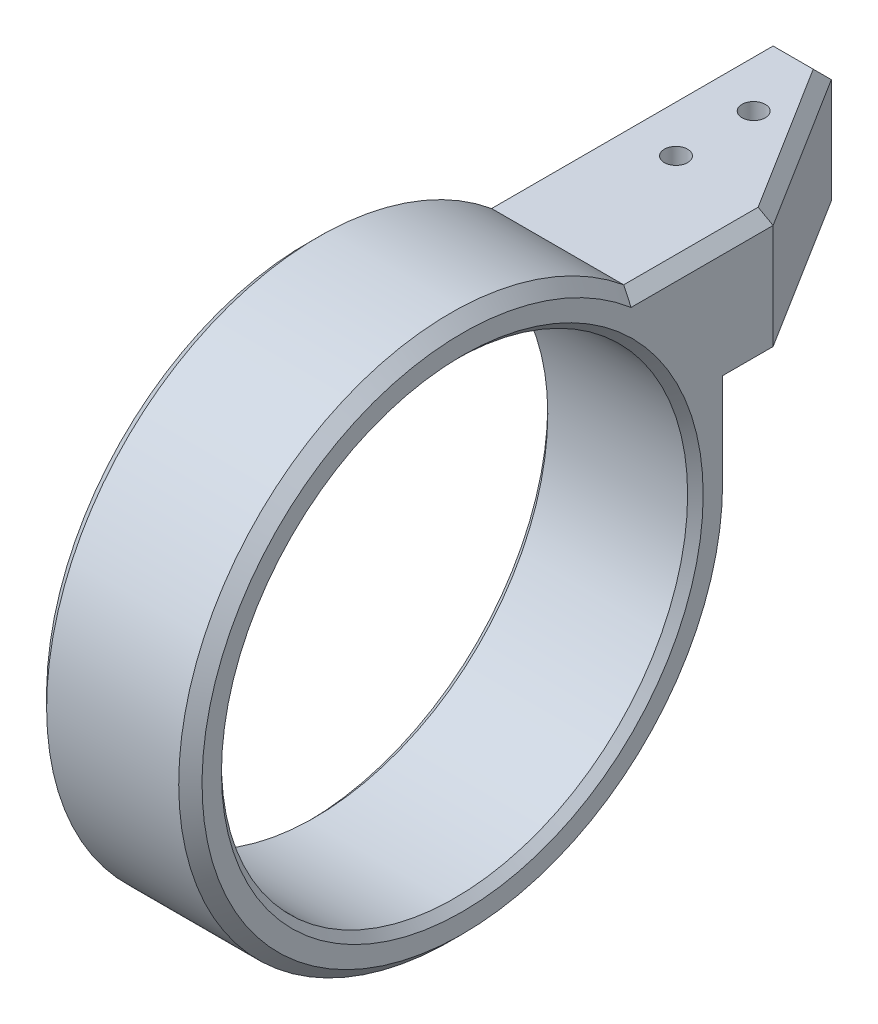
SolidWorks part; units mm, degrees
ref_plane "Front" through (0, 0, 0) normal (0, 0, 1) x (1, 0, 0)
ref_plane "Top" through (0, 0, 0) normal (0, 1, 0) x (1, 0, 0)
ref_plane "Right" through (0, 0, 0) normal (1, 0, 0) x (0, 0, -1)
sketch "草图1" plane through (0, 0, 0) normal (1, 0, 0) x (0, 0, -1)
  circle A0 centre (0, 0) radius 35
  dimension "D1" = 70
extrude "凸台-拉伸1" add sketch "草图1" along normal blind 20
sketch "草图2" plane through (20, 0, 0) normal (1, 0, 0) x (0, 0, -1)
  circle A0 centre (0, 0) radius 30
  circle A1 centre (0, 0) radius 35 construction
  dimension "D1" = 60
extrude "切除-拉伸1" cut sketch "草图2" against normal through all
ref_plane "基准面1" through (0, 0, -35) normal (0, 0, -1) x (-1, 0, 0)
sketch "草图3" plane through (0, 0, -35) normal (0, 0, -1) x (-1, 0, 0)
  line L0 (-20, 35) -> (-20, -35) construction
  line L1 (0, 12) -> (-20, 12)
  line L2 (0, 12) -> (0, 27)
  line L3 (0, 27) -> (-20, 27)
  line L4 (-20, 12) -> (-20, 27)
  line L5 (0, 12) -> (-20, 27) construction
  line L6 (0, 27) -> (-20, 12) construction
  line L7 (0, -35) -> (0, 35) construction
  line L8 (0, 0) -> (-20, 0) construction
  point P0 (-10, 19.5)
  dimension "D1" = 12
  dimension "D2" = 15
extrude "凸台-拉伸2" add sketch "草图3" along normal mid plane 50
sketch "草图4" plane through (0, 0, -35) normal (0, 0, -1) x (-1, 0, 0)
  line L0 (-20, 35) -> (-20, -35) construction
  line L1 (0, 0) -> (-20, 0)
  line L2 (0, 0) -> (0, 12)
  line L3 (0, 12) -> (-20, 12)
  line L4 (-20, 0) -> (-20, 12)
  line L5 (0, 0) -> (-20, 12) construction
  line L6 (0, 12) -> (-20, 0) construction
  line L7 (0, -35) -> (0, 35) construction
  line L8 (-20, 12) -> (0, 12) construction
  line L9 (0, 0) -> (-20, 0) construction
  point P0 (-10, 6)
extrude "凸台-拉伸3" add sketch "草图4" against normal up to surface up to face at (10, -0.3542, 0.5009)
sketch "草图5" plane through (20, 0, 0) normal (1, 0, 0) x (0, 0, -1)
  circle A0 centre (0, 0) radius 30
  arc A1 (13.0767, 27) -> (27.4955, 12) centre (0, 0) ccw construction
extrude "切除-拉伸2" cut sketch "草图5" against normal through all
sketch "草图6" plane through (0, 27, 0) normal (0, 1, 0) x (1, 0, 0)
  line L0 (7.5, 60) -> (20, 40)
  line L1 (0, 60) -> (20, 60) construction
  line L2 (20, 60) -> (20, 22.2711) construction
  line L3 (0, 60) -> (0, 22.2711) construction
  line L4 (7.5, 60) -> (20, 60)
  line L5 (20, 60) -> (20, 40)
  dimension "D1" = 7.5
  dimension "D2" = 20
extrude "切除-拉伸3" cut sketch "草图6" against normal up to next
sketch "草图8" plane through (0, 12, 0) normal (0, -1, 0) x (-1, 0, 0)
  line L0 (-7.5, 60) -> (-7.5, 35) construction
  line L1 (0, 35) -> (-20, 35) construction
  circle A0 centre (-7.5, 40) radius 1.5
  circle A1 centre (-7.5, 50) radius 1.5
  dimension "D1" = 3
  dimension "D2" = 3
  dimension "D3" = 5
  dimension "D4" = 15
extrude "切除-拉伸4" cut sketch "草图8" against normal through all
chamfer "倒角1" distance 1 angle 45 2 edges at (0, 0, -30) (20, 0, -30)
chamfer "倒角2" distance 1.5 angle 45 8 edges at (0, 6, -35) (20, 6, -35) (20, -14.925, 31.6582) (0, -14.925, 31.6582) (0, 27, -41.1355) (3.75, 27, -60) (13.75, 27, -50) (20, 27, -31.1355)
